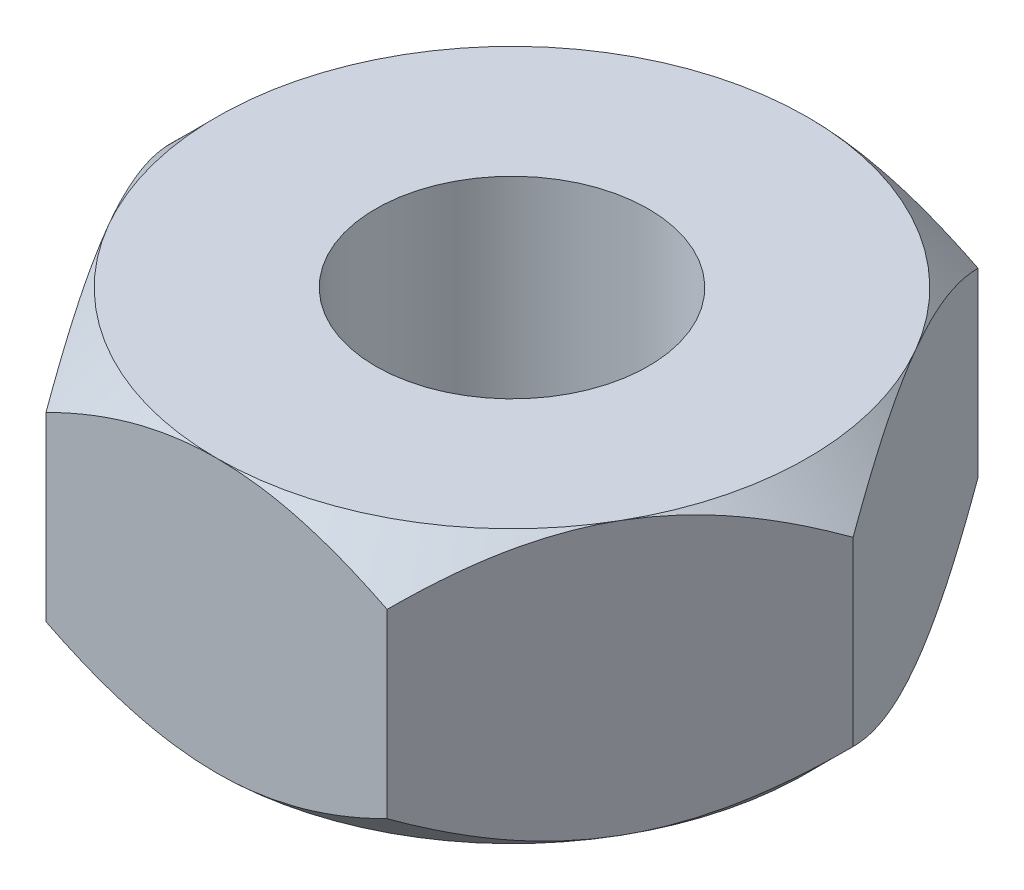
SolidWorks part; units mm, degrees
material "AISI 1045 Steel, cold drawn"
ref_plane "Front Plane" through (0, 0, 0) normal (0, 0, 1) x (1, 0, 0)
ref_plane "Top Plane" through (0, 0, 0) normal (0, 1, 0) x (1, 0, 0)
ref_plane "Right Plane" through (0, 0, 0) normal (1, 0, 0) x (0, 0, -1)
sketch "Sketch2" plane through (0, 0, 0) normal (0, 1, 0) x (1, 0, 0)
  line L1 (-15.0111, 0) -> (-7.5056, -13)
  line L2 (-7.5056, -13) -> (7.5056, -13)
  line L3 (7.5056, -13) -> (15.0111, 0)
  line L4 (15.0111, 0) -> (7.5056, 13)
  line L5 (7.5056, 13) -> (-7.5056, 13)
  line L6 (-7.5056, 13) -> (-15.0111, 0)
  circle A0 centre (0, 0) radius 13 construction
  dimension "D1" = 26
extrude "Boss-Extrude1" add sketch "Sketch2" along normal blind 12
sketch "Sketch3" plane through (0, 12, 0) normal (0, 1, 0) x (1, 0, 0)
  circle A0 centre (0, 0) radius 6
  dimension "D1" = 12
extrude "Cut-Extrude1" cut sketch "Sketch3" against normal through all contours A0
sketch "Sketch6" plane through (0, 12, 0) normal (0, 1, 0) x (1, 0, 0)
  circle A0 centre (0, 0) radius 13
  dimension "D1" = 26
extrude "Cut-Extrude3" cut sketch "Sketch6" against normal through all draft 45 flip side to cut
sketch "Sketch7" plane through (0, 0, 0) normal (0, -1, 0) x (1, 0, 0)
  circle A0 centre (0, 0) radius 13
  dimension "D1" = 26
extrude "Cut-Extrude4" cut sketch "Sketch7" against normal through all draft 45 flip side to cut
